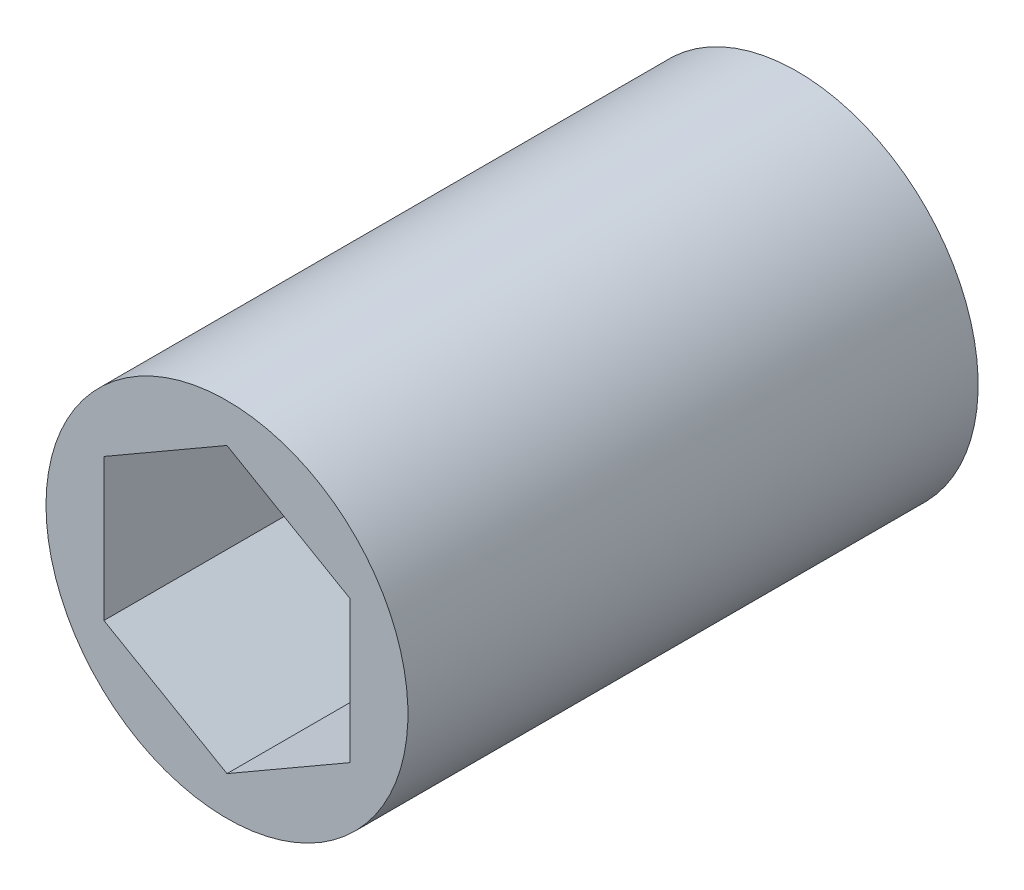
SolidWorks part; units mm, degrees
material "PET"
ref_plane "Front Plane" through (0, 0, 0) normal (0, 0, 1) x (1, 0, 0)
ref_plane "Top Plane" through (0, 0, 0) normal (0, 1, 0) x (1, 0, 0)
ref_plane "Right Plane" through (0, 0, 0) normal (1, 0, 0) x (0, 0, -1)
sketch "Sketch1" plane through (0, 0, 0) normal (0, 0, 1) x (1, 0, 0)
  line L1 (0, 7.479) -> (-6.477, 3.7395)
  line L2 (-6.477, 3.7395) -> (-6.477, -3.7395)
  line L3 (-6.477, -3.7395) -> (0, -7.479)
  line L4 (0, -7.479) -> (6.477, -3.7395)
  line L5 (6.477, -3.7395) -> (6.477, 3.7395)
  line L6 (6.477, 3.7395) -> (0, 7.479)
  circle A0 centre (0, 0) radius 9.525
  circle A1 centre (0, 0) radius 6.477 construction
  dimension "D1" = 12.954
  dimension "D2" = 19.05
extrude "Boss-Extrude1" add sketch "Sketch1" along normal blind 30.0126
